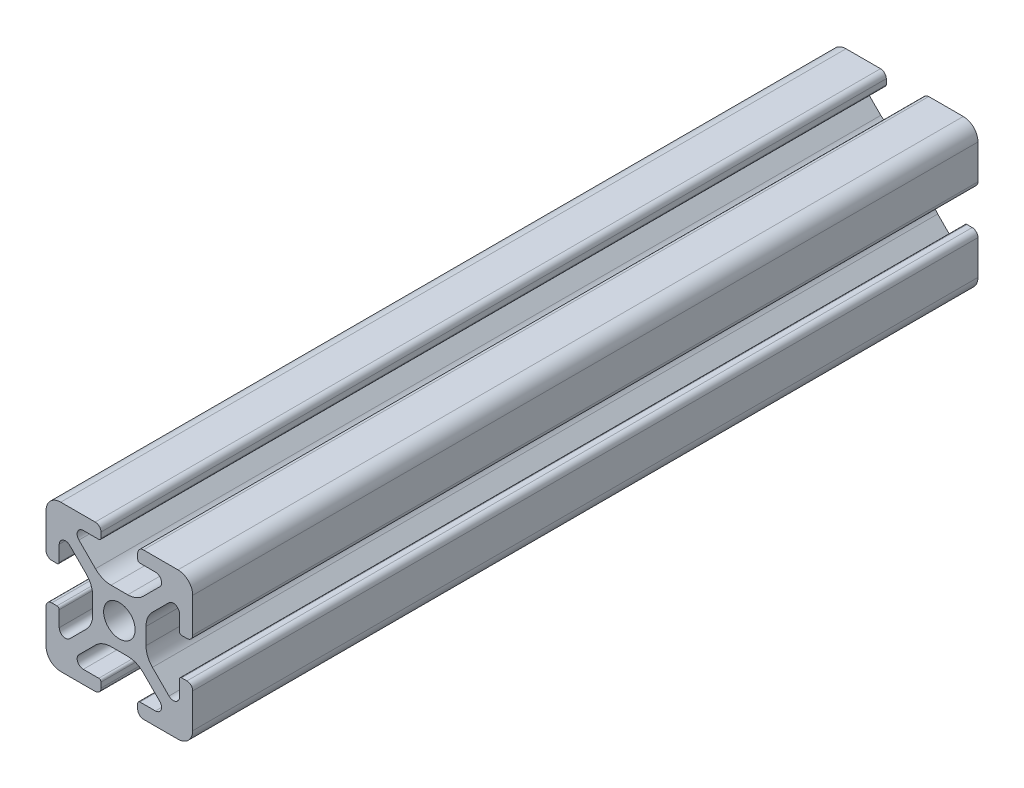
SolidWorks part; units mm, degrees
ref_plane "Front Plane" through (0, 0, 0) normal (0, 0, 1) x (1, 0, 0)
ref_plane "Top Plane" through (0, 0, 0) normal (0, 1, 0) x (1, 0, 0)
ref_plane "Right Plane" through (0, 0, 0) normal (1, 0, 0) x (0, 0, -1)
sketch "Sketch1" plane through (0, 0, 0) normal (0, 0, 1) x (1, 0, 0)
  line L2 (-9.9949, 7.9883) -> (-9.9949, 3.2893)
  line L3 (-7.9883, 9.9949) -> (-3.2893, 9.9949)
  line L4 (-2.5019, 9.2075) -> (-2.5019, 8.4963)
  line L5 (-2.8067, 8.1915) -> (-4.9149, 8.1915)
  line L6 (-5.5076, 6.7606) -> (-3.2528, 4.5058)
  line L7 (-6.7606, 5.5076) -> (-4.5058, 3.2528)
  line L8 (-8.1915, 4.9149) -> (-8.1915, 2.8067)
  line L9 (-8.4963, 2.5019) -> (-9.2075, 2.5019)
  line L11 (-1.1334, 3.6279) -> (1.1334, 3.6279)
  line L12 (-3.6279, 1.1334) -> (-3.6279, -1.1334)
  line L13 (8.4963, 2.5019) -> (9.2075, 2.5019)
  line L14 (8.1915, 4.9149) -> (8.1915, 2.8067)
  line L15 (9.9949, 7.9883) -> (9.9949, 3.2893)
  line L16 (7.9883, 9.9949) -> (3.2893, 9.9949)
  line L17 (2.5019, 9.2075) -> (2.5019, 8.4963)
  line L18 (2.8067, 8.1915) -> (4.9149, 8.1915)
  line L19 (3.6279, 1.1334) -> (3.6279, -1.1334)
  line L20 (5.5076, 6.7606) -> (3.2528, 4.5058)
  line L21 (6.7606, 5.5076) -> (4.5058, 3.2528)
  line L22 (-8.4963, -2.5019) -> (-9.2075, -2.5019)
  line L23 (-8.1915, -4.9149) -> (-8.1915, -2.8067)
  line L24 (-6.7606, -5.5076) -> (-4.5058, -3.2528)
  line L25 (-5.5076, -6.7606) -> (-3.2528, -4.5058)
  line L26 (-2.8067, -8.1915) -> (-4.9149, -8.1915)
  line L27 (-2.5019, -9.2075) -> (-2.5019, -8.4963)
  line L28 (-7.9883, -9.9949) -> (-3.2893, -9.9949)
  line L29 (-9.9949, -7.9883) -> (-9.9949, -3.2893)
  line L30 (9.9949, -7.9883) -> (9.9949, -3.2893)
  line L31 (7.9883, -9.9949) -> (3.2893, -9.9949)
  line L32 (2.5019, -9.2075) -> (2.5019, -8.4963)
  line L33 (2.8067, -8.1915) -> (4.9149, -8.1915)
  line L34 (5.5076, -6.7606) -> (3.2528, -4.5058)
  line L35 (6.7606, -5.5076) -> (4.5058, -3.2528)
  line L36 (8.1915, -4.9149) -> (8.1915, -2.8067)
  line L37 (8.4963, -2.5019) -> (9.2075, -2.5019)
  line L38 (-1.1334, -3.6279) -> (1.1334, -3.6279)
  circle A0 centre (0, 0) radius 2.1463
  arc A1 (-9.9949, 7.9883) -> (-7.9883, 9.9949) centre (-7.9883, 7.9883) cw
  arc A2 (-6.7606, 5.5076) -> (-8.1915, 4.9149) centre (-7.3533, 4.9149) ccw
  arc A3 (-4.9149, 8.1915) -> (-5.5076, 6.7606) centre (-4.9149, 7.3533) ccw
  arc A4 (-3.2893, 9.9949) -> (-2.5019, 9.2075) centre (-3.2893, 9.2075) cw
  arc A5 (-9.9949, 3.2893) -> (-9.2075, 2.5019) centre (-9.2075, 3.2893) ccw
  arc A6 (-8.1915, 2.8067) -> (-8.4963, 2.5019) centre (-8.4963, 2.8067) cw
  arc A7 (-2.5019, 8.4963) -> (-2.8067, 8.1915) centre (-2.8067, 8.4963) cw
  arc A8 (-1.1334, 3.6279) -> (-3.2528, 4.5058) centre (-1.1334, 6.6251) cw
  arc A9 (-3.6279, 1.1334) -> (-4.5058, 3.2528) centre (-6.6251, 1.1334) ccw
  arc A10 (8.1915, 2.8067) -> (8.4963, 2.5019) centre (8.4963, 2.8067) ccw
  arc A11 (9.9949, 3.2893) -> (9.2075, 2.5019) centre (9.2075, 3.2893) cw
  arc A12 (9.9949, 7.9883) -> (7.9883, 9.9949) centre (7.9883, 7.9883) ccw
  arc A13 (3.2893, 9.9949) -> (2.5019, 9.2075) centre (3.2893, 9.2075) ccw
  arc A14 (2.5019, 8.4963) -> (2.8067, 8.1915) centre (2.8067, 8.4963) ccw
  arc A15 (1.1334, 3.6279) -> (3.2528, 4.5058) centre (1.1334, 6.6251) ccw
  arc A16 (3.6279, 1.1334) -> (4.5058, 3.2528) centre (6.6251, 1.1334) cw
  arc A17 (6.7606, 5.5076) -> (8.1915, 4.9149) centre (7.3533, 4.9149) cw
  arc A18 (4.9149, 8.1915) -> (5.5076, 6.7606) centre (4.9149, 7.3533) cw
  arc A19 (-3.6279, -1.1334) -> (-4.5058, -3.2528) centre (-6.6251, -1.1334) cw
  arc A20 (-1.1334, -3.6279) -> (-3.2528, -4.5058) centre (-1.1334, -6.6251) ccw
  arc A21 (-2.5019, -8.4963) -> (-2.8067, -8.1915) centre (-2.8067, -8.4963) ccw
  arc A22 (-8.1915, -2.8067) -> (-8.4963, -2.5019) centre (-8.4963, -2.8067) ccw
  arc A23 (-9.9949, -3.2893) -> (-9.2075, -2.5019) centre (-9.2075, -3.2893) cw
  arc A24 (-3.2893, -9.9949) -> (-2.5019, -9.2075) centre (-3.2893, -9.2075) ccw
  arc A25 (-4.9149, -8.1915) -> (-5.5076, -6.7606) centre (-4.9149, -7.3533) cw
  arc A26 (-6.7606, -5.5076) -> (-8.1915, -4.9149) centre (-7.3533, -4.9149) cw
  arc A27 (-9.9949, -7.9883) -> (-7.9883, -9.9949) centre (-7.9883, -7.9883) ccw
  arc A28 (9.9949, -7.9883) -> (7.9883, -9.9949) centre (7.9883, -7.9883) cw
  arc A29 (6.7606, -5.5076) -> (8.1915, -4.9149) centre (7.3533, -4.9149) ccw
  arc A30 (4.9149, -8.1915) -> (5.5076, -6.7606) centre (4.9149, -7.3533) ccw
  arc A31 (3.2893, -9.9949) -> (2.5019, -9.2075) centre (3.2893, -9.2075) cw
  arc A32 (9.9949, -3.2893) -> (9.2075, -2.5019) centre (9.2075, -3.2893) ccw
  arc A33 (8.1915, -2.8067) -> (8.4963, -2.5019) centre (8.4963, -2.8067) cw
  arc A34 (2.5019, -8.4963) -> (2.8067, -8.1915) centre (2.8067, -8.4963) cw
  arc A35 (1.1334, -3.6279) -> (3.2528, -4.5058) centre (1.1334, -6.6251) cw
  arc A36 (3.6279, -1.1334) -> (4.5058, -3.2528) centre (6.6251, -1.1334) ccw
extrude "Boss-Extrude1" add sketch "Sketch1" along normal mid plane 106.9975
